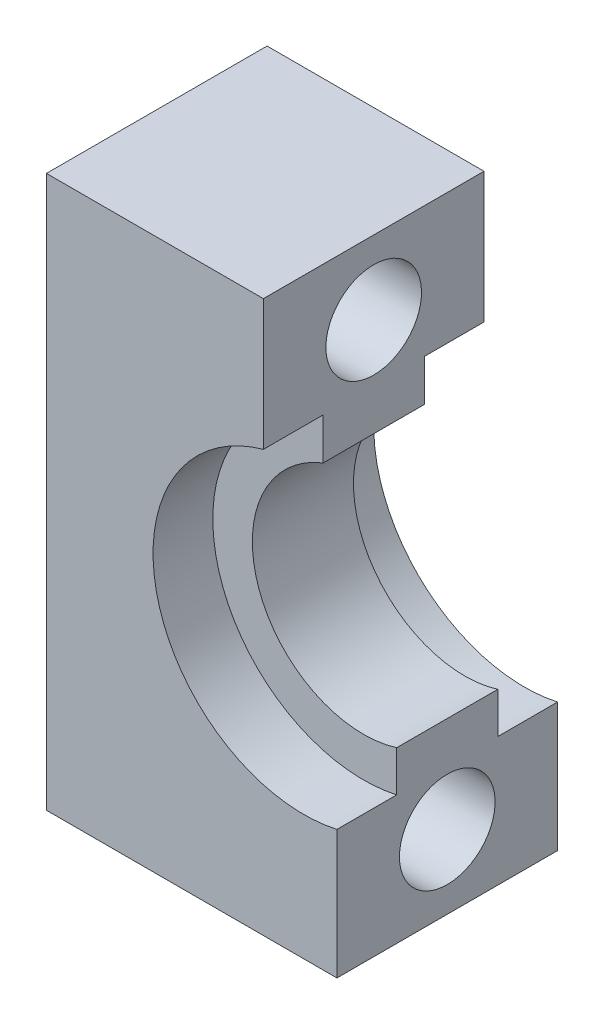
SolidWorks part; units mm, degrees
ref_plane "Front Plane" through (0, 0, 0) normal (0, 0, 1) x (1, 0, 0)
ref_plane "Top Plane" through (0, 0, 0) normal (0, 1, 0) x (1, 0, 0)
ref_plane "Right Plane" through (0, 0, 0) normal (1, 0, 0) x (0, 0, -1)
sketch "Sketch3" plane through (0, 0, 0) normal (0, 0, 1) x (1, 0, 0)
  line L0 (0, -15) -> (0, 15)
  line L1 (0, 15) -> (11.8, 15)
  line L2 (0, -15) -> (15.8, -15)
  line L3 (5.5, 0) -> (-5.5, 0) construction
  line L4 (0, -5.5) -> (0, 5.5) construction
  line L5 (11.8, 15) -> (11.8, 7.8994)
  line L6 (15.8, -15) -> (15.8, -8)
  arc A0 (11.8, 7.8994) -> (15.8, -8) centre (14, 0) ccw
  dimension "D1" = 16.4
  dimension "D2" = 30
  dimension "D3" = 15
  dimension "D4" = 14
  dimension "D5" = 11.8
  dimension "D6" = 15.8
extrude "Boss-Extrude2" add sketch "Sketch3" along normal mid plane 12
sketch "Sketch4" plane through (0, 0, 0) normal (0, 0, 1) x (1, 0, 0)
  line L0 (11.8, 8.2104) -> (11.8, 5.6358)
  line L1 (15.8, -5.776) -> (15.8, -8.3072)
  arc A0 (11.8, 5.6358) -> (15.8, -5.776) centre (14, 0) ccw
  arc A1 (11.8, 8.2104) -> (15.8, -8.3072) centre (14, 0) ccw
  dimension "D1" = 12.1
  dimension "D2" = 17
  dimension "D3" = 2.2
  dimension "D4" = 1.8
extrude "Boss-Extrude3" add sketch "Sketch4" along normal mid plane 5.5
sketch "Sketch5" plane through (0, 0, 0) normal (1, 0, 0) x (0, 0, -1)
  line L0 (0, 8.8) -> (0, -8.8) construction
  line L1 (5.5, 0) -> (-5.5, 0) construction
  circle A0 centre (0, 11) radius 2.6
  circle A1 centre (0, -11) radius 2.6
  dimension "D1" = 5.2
  dimension "D2" = 5.2
  dimension "D3" = 11
  dimension "D4" = 11
extrude "Cut-Extrude1" cut sketch "Sketch5" along normal up to next
